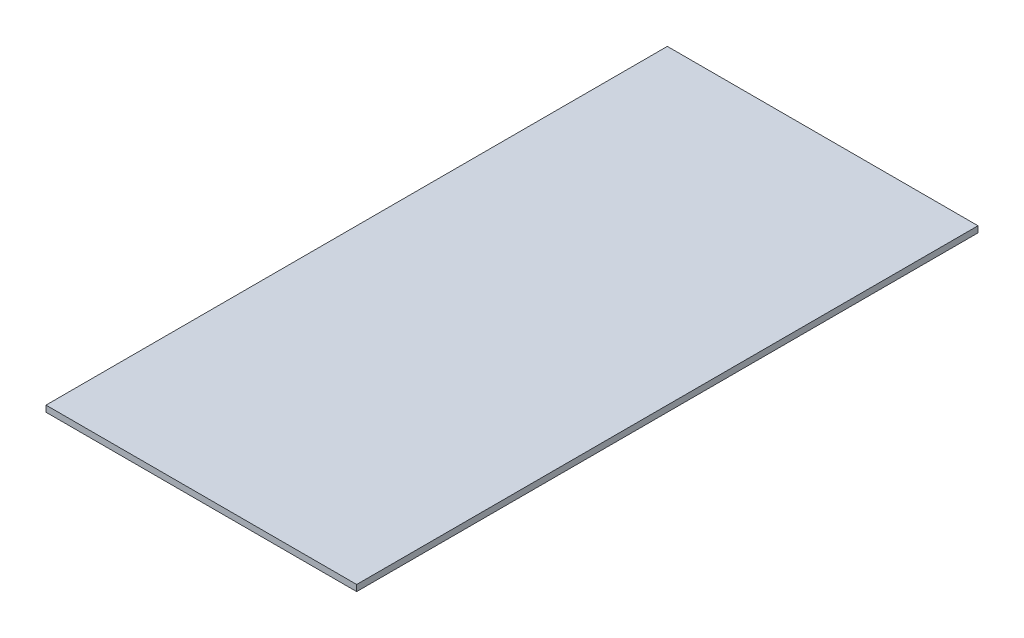
SolidWorks part; units mm, degrees
ref_plane "Front Plane" through (0, 0, 0) normal (0, 0, 1) x (1, 0, 0)
ref_plane "Top Plane" through (0, 0, 0) normal (0, 1, 0) x (1, 0, 0)
ref_plane "Right Plane" through (0, 0, 0) normal (1, 0, 0) x (0, 0, -1)
sketch "Sketch1" plane through (0, 0, 0) normal (0, 1, 0) x (1, 0, 0)
  line L1 (-5209.0909, 2795.4545) -> (-4909.0909, 2795.4545)
  line L2 (-5209.0909, 2795.4545) -> (-5209.0909, 2195.4545)
  line L3 (-5209.0909, 2195.4545) -> (-4909.0909, 2195.4545)
  line L4 (-4909.0909, 2795.4545) -> (-4909.0909, 2195.4545)
  dimension "D1" = 300
  dimension "D2" = 600
extrude "Boss-Extrude1" add sketch "Sketch1" along normal blind 6
